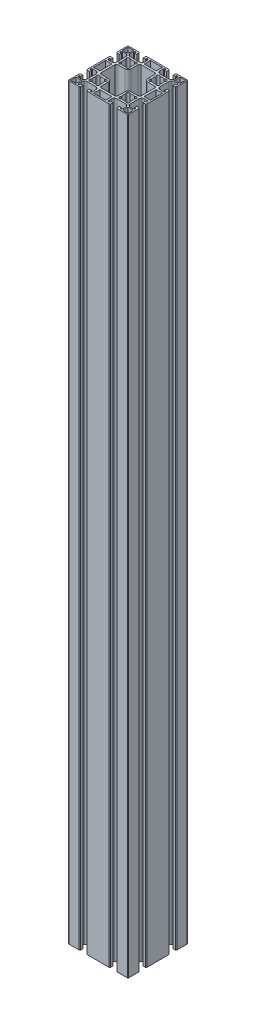
SolidWorks part; units mm, degrees
ref_plane "Front Plane" through (0, 0, 0) normal (0, 0, 1) x (1, 0, 0)
ref_plane "Top Plane" through (0, 0, 0) normal (0, 1, 0) x (1, 0, 0)
ref_plane "Right Plane" through (0, 0, 0) normal (1, 0, 0) x (0, 0, -1)
sketch "Sketch1" plane through (0, 0, 0) normal (0, 1, 0) x (1, 0, 0)
  line L0 (16.5224, 10.1082) -> (17.1083, 10.6941)
  line L2 (14.2799, 13.5226) -> (13.694, 12.9366)
  line L7 (13.694, 19.6541) -> (14.2799, 19.0682)
  line L8 (17.1083, 21.8966) -> (16.5224, 22.4826)
  line L9 (23.2399, 22.4826) -> (22.654, 21.8966)
  line L10 (25.4824, 19.0682) -> (26.0683, 19.6541)
  line L11 (26.0683, 12.9366) -> (25.4824, 13.5226)
  line L12 (22.654, 10.6941) -> (23.2399, 10.1082)
  line L13 (-29.7188, -11.8046) -> (-29.7188, 4.3954)
  line L14 (-38.1188, -11.8046) -> (-29.7188, -11.8046)
  line L15 (-38.1188, 4.3954) -> (-38.1188, -11.8046)
  line L16 (-29.7188, 4.3954) -> (-38.1188, 4.3954)
  line L17 (-23.4776, 10.1082) -> (-22.8917, 10.6941)
  line L18 (-25.7201, 13.5226) -> (-26.306, 12.9366)
  line L19 (-26.306, 19.6541) -> (-25.7201, 19.0682)
  line L20 (-22.8917, 21.8966) -> (-23.4776, 22.4826)
  line L21 (-16.7601, 22.4826) -> (-17.346, 21.8966)
  line L22 (-14.5176, 19.0682) -> (-13.9317, 19.6541)
  line L23 (-13.9317, 12.9366) -> (-14.5176, 13.5226)
  line L24 (-17.346, 10.6941) -> (-16.7601, 10.1082)
  line L26 (23.2399, -17.5174) -> (22.654, -18.1034)
  line L27 (25.4824, -20.9318) -> (26.0683, -20.3459)
  line L28 (26.0683, -27.0634) -> (25.4824, -26.4774)
  line L29 (22.654, -29.3059) -> (23.2399, -29.8918)
  line L30 (16.5224, -29.8918) -> (17.1083, -29.3059)
  line L31 (14.2799, -26.4774) -> (13.694, -27.0634)
  line L32 (13.694, -20.3459) -> (14.2799, -20.9318)
  line L33 (17.1083, -18.1034) -> (16.5224, -17.5174)
  line L41 (-31.3188, -34.9046) -> (-38.5188, -34.9046)
  line L42 (-31.3188, -42.1046) -> (-31.3188, -34.9046)
  line L43 (-38.5188, -42.1046) -> (-31.3188, -42.1046)
  line L44 (-38.5188, -34.9046) -> (-38.5188, -42.1046)
  line L45 (-16.7601, -17.5174) -> (-17.346, -18.1034)
  line L46 (-14.5176, -20.9318) -> (-13.9317, -20.3459)
  line L51 (-13.9317, -27.0634) -> (-14.5176, -26.4774)
  line L52 (-17.346, -29.3059) -> (-16.7601, -29.8918)
  line L53 (-23.4776, -29.8918) -> (-22.8917, -29.3059)
  line L54 (-25.7201, -26.4774) -> (-26.306, -27.0634)
  line L55 (-26.306, -20.3459) -> (-25.7201, -20.9318)
  line L56 (-22.8917, -18.1034) -> (-23.4776, -17.5174)
  line L57 (-38.5188, 27.4954) -> (-31.3188, 27.4954)
  line L58 (-38.5188, 34.6954) -> (-38.5188, 27.4954)
  line L59 (-31.3188, 34.6954) -> (-38.5188, 34.6954)
  line L60 (-31.3188, 27.4954) -> (-31.3188, 34.6954)
  line L61 (38.2812, -34.9046) -> (31.0812, -34.9046)
  line L62 (38.2812, -42.1046) -> (38.2812, -34.9046)
  line L63 (31.0812, -42.1046) -> (38.2812, -42.1046)
  line L64 (31.0812, -34.9046) -> (31.0812, -42.1046)
  line L65 (31.0812, 27.4954) -> (38.2812, 27.4954)
  line L66 (31.0812, 34.6954) -> (31.0812, 27.4954)
  line L67 (38.2812, 34.6954) -> (31.0812, 34.6954)
  line L68 (38.2812, 27.4954) -> (38.2812, 34.6954)
  line L69 (-8.2188, 34.2954) -> (-8.2188, 25.8954)
  line L70 (7.9812, 34.2954) -> (-8.2188, 34.2954)
  line L71 (7.9812, 25.8954) -> (7.9812, 34.2954)
  line L72 (-8.2188, 25.8954) -> (7.9812, 25.8954)
  line L79 (11.0812, -28.5046) -> (11.0812, -18.9046)
  line L80 (-9.3188, -30.5046) -> (9.0812, -30.5046)
  line L81 (-11.3188, -18.9046) -> (-11.3188, -28.5046)
  line L82 (-24.9188, -14.9046) -> (-15.3188, -14.9046)
  line L83 (-26.9188, 5.4954) -> (-26.9188, -12.9046)
  line L84 (-15.3188, 7.4954) -> (-24.9188, 7.4954)
  line L89 (-11.3188, 21.0954) -> (-11.3188, 11.4954)
  line L90 (9.0812, 23.0954) -> (-9.3188, 23.0954)
  line L91 (11.0812, 11.4954) -> (11.0812, 21.0954)
  line L92 (24.6812, 7.4954) -> (15.0812, 7.4954)
  line L93 (26.6812, -12.9046) -> (26.6812, 5.4954)
  line L94 (15.0812, -14.9046) -> (24.6812, -14.9046)
  line L95 (7.9812, -33.3046) -> (-8.2188, -33.3046)
  line L96 (7.9812, -41.7046) -> (7.9812, -33.3046)
  line L97 (-8.2188, -41.7046) -> (7.9812, -41.7046)
  line L98 (-8.2188, -33.3046) -> (-8.2188, -41.7046)
  line L99 (29.4812, 4.3954) -> (29.4812, -11.8046)
  line L100 (37.8812, 4.3954) -> (29.4812, 4.3954)
  line L101 (37.8812, -11.8046) -> (37.8812, 4.3954)
  line L102 (29.4812, -11.8046) -> (37.8812, -11.8046)
  line L103 (39.8812, -42.7046) -> (39.8812, -28.9546)
  line L104 (39.8812, -28.9546) -> (38.8812, -27.9546)
  line L105 (38.8812, -27.9546) -> (35.8812, -27.9546)
  line L106 (35.8812, -27.9546) -> (35.8812, -30.9546)
  line L107 (35.8812, -30.9546) -> (37.4853, -30.9546)
  line L108 (37.9777, -31.5414) -> (37.7979, -32.5609)
  line L109 (36.9116, -33.3046) -> (32.215, -33.3046)
  line L110 (30.0937, -32.4259) -> (29.5598, -31.8921)
  line L111 (28.6812, -29.7708) -> (28.6812, -17.6385)
  line L118 (29.5598, -15.5172) -> (30.0937, -14.9833)
  line L119 (32.215, -14.1046) -> (36.9116, -14.1046)
  line L120 (37.7979, -14.8483) -> (37.9777, -15.8678)
  line L121 (37.4853, -16.4546) -> (35.8812, -16.4546)
  line L122 (35.8812, -16.4546) -> (35.8812, -19.4546)
  line L123 (35.8812, -19.4546) -> (38.8812, -19.4546)
  line L128 (38.8812, -19.4546) -> (39.8812, -18.4546)
  line L129 (39.8812, -18.4546) -> (39.8812, 11.0454)
  line L130 (39.8812, 11.0454) -> (38.8812, 12.0454)
  line L131 (38.8812, 12.0454) -> (35.8812, 12.0454)
  line L132 (35.8812, 12.0454) -> (35.8812, 9.0454)
  line L133 (35.8812, 9.0454) -> (37.4853, 9.0454)
  line L134 (37.9777, 8.4586) -> (37.7979, 7.4391)
  line L135 (36.9116, 6.6954) -> (32.215, 6.6954)
  line L136 (30.0937, 7.5741) -> (29.5598, 8.1079)
  line L137 (28.6812, 10.2292) -> (28.6812, 22.3615)
  line L138 (29.5598, 24.4828) -> (30.0937, 25.0167)
  line L139 (32.215, 25.8954) -> (36.9116, 25.8954)
  line L140 (37.7979, 25.1517) -> (37.9777, 24.1322)
  line L141 (37.4853, 23.5454) -> (35.8812, 23.5454)
  line L142 (35.8812, 23.5454) -> (35.8812, 20.5454)
  line L143 (35.8812, 20.5454) -> (38.8812, 20.5454)
  line L144 (38.8812, 20.5454) -> (39.8812, 21.5454)
  line L145 (39.8812, 21.5454) -> (39.8812, 35.2954)
  line L146 (38.8812, 36.2954) -> (25.1312, 36.2954)
  line L147 (25.1312, 36.2954) -> (24.1312, 35.2954)
  line L148 (24.1312, 35.2954) -> (24.1312, 32.2954)
  line L149 (24.1312, 32.2954) -> (27.1312, 32.2954)
  line L150 (27.1312, 32.2954) -> (27.1312, 33.8995)
  line L157 (27.718, 34.3919) -> (28.7374, 34.2122)
  line L158 (29.4812, 33.3258) -> (29.4812, 28.6292)
  line L159 (28.6025, 26.5079) -> (28.0686, 25.9741)
  line L160 (25.9473, 25.0954) -> (13.815, 25.0954)
  line L161 (11.6937, 25.9741) -> (11.1598, 26.5079)
  line L162 (10.2812, 28.6292) -> (10.2812, 33.3258)
  line L167 (11.0249, 34.2122) -> (12.0443, 34.3919)
  line L172 (12.6312, 33.8995) -> (12.6312, 32.2954)
  line L173 (12.6312, 32.2954) -> (15.6312, 32.2954)
  line L178 (15.6312, 32.2954) -> (15.6312, 35.2954)
  line L179 (15.6312, 35.2954) -> (14.6312, 36.2954)
  line L183 (14.6312, 36.2954) -> (-14.8688, 36.2954)
  line L184 (-14.8688, 36.2954) -> (-15.8688, 35.2954)
  line L189 (-15.8688, 35.2954) -> (-15.8688, 32.2954)
  line L190 (-15.8688, 32.2954) -> (-12.8688, 32.2954)
  line L195 (-12.8688, 32.2954) -> (-12.8688, 33.8995)
  line L196 (-12.282, 34.3919) -> (-11.2626, 34.2122)
  line L198 (-10.5188, 33.3258) -> (-10.5188, 28.6292)
  line L199 (-11.3975, 26.5079) -> (-11.9314, 25.9741)
  line L200 (-14.0527, 25.0954) -> (-26.185, 25.0954)
  line L201 (-28.3063, 25.9741) -> (-28.8402, 26.5079)
  line L202 (-29.7188, 28.6292) -> (-29.7188, 33.3258)
  line L203 (-28.9751, 34.2122) -> (-27.9557, 34.3919)
  line L204 (-27.3688, 33.8995) -> (-27.3688, 32.2954)
  line L205 (-27.3688, 32.2954) -> (-24.3688, 32.2954)
  line L206 (-24.3688, 32.2954) -> (-24.3688, 35.2954)
  line L207 (-24.3688, 35.2954) -> (-25.3688, 36.2954)
  line L208 (-25.3688, 36.2954) -> (-39.1188, 36.2954)
  line L209 (-40.1188, 35.2954) -> (-40.1188, 21.5454)
  line L210 (-40.1188, 21.5454) -> (-39.1188, 20.5454)
  line L211 (-39.1188, 20.5454) -> (-36.1188, 20.5454)
  line L212 (-36.1188, 20.5454) -> (-36.1188, 23.5454)
  line L213 (-36.1188, 23.5454) -> (-37.723, 23.5454)
  line L214 (-38.2154, 24.1322) -> (-38.0356, 25.1517)
  line L215 (-37.1493, 25.8954) -> (-32.4527, 25.8954)
  line L216 (-30.3314, 25.0167) -> (-29.7975, 24.4828)
  line L217 (-28.9188, 22.3615) -> (-28.9188, 10.2292)
  line L218 (-29.7975, 8.1079) -> (-30.3314, 7.5741)
  line L219 (-32.4527, 6.6954) -> (-37.1493, 6.6954)
  line L220 (-38.0356, 7.4391) -> (-38.2154, 8.4586)
  line L221 (-37.723, 9.0454) -> (-36.1188, 9.0454)
  line L222 (-36.1188, 9.0454) -> (-36.1188, 12.0454)
  line L223 (-36.1188, 12.0454) -> (-39.1188, 12.0454)
  line L224 (-39.1188, 12.0454) -> (-40.1188, 11.0454)
  line L225 (-40.1188, 11.0454) -> (-40.1188, -18.4546)
  line L226 (-40.1188, -18.4546) -> (-39.1188, -19.4546)
  line L227 (-39.1188, -19.4546) -> (-36.1188, -19.4546)
  line L228 (-36.1188, -19.4546) -> (-36.1188, -16.4546)
  line L229 (-36.1188, -16.4546) -> (-37.723, -16.4546)
  line L230 (-38.2154, -15.8678) -> (-38.0356, -14.8483)
  line L231 (-37.1493, -14.1046) -> (-32.4527, -14.1046)
  line L232 (-30.3314, -14.9833) -> (-29.7975, -15.5172)
  line L233 (-28.9188, -17.6385) -> (-28.9188, -29.7708)
  line L234 (-29.7975, -31.8921) -> (-30.3314, -32.4259)
  line L235 (-32.4527, -33.3046) -> (-37.1493, -33.3046)
  line L236 (-38.0356, -32.5609) -> (-38.2154, -31.5414)
  line L237 (-37.723, -30.9546) -> (-36.1188, -30.9546)
  line L238 (-36.1188, -30.9546) -> (-36.1188, -27.9546)
  line L239 (-36.1188, -27.9546) -> (-39.1188, -27.9546)
  line L240 (-39.1188, -27.9546) -> (-40.1188, -28.9546)
  line L241 (-40.1188, -28.9546) -> (-40.1188, -42.7046)
  line L242 (-39.1188, -43.7046) -> (-25.3688, -43.7046)
  line L243 (-25.3688, -43.7046) -> (-24.3688, -42.7046)
  line L244 (-24.3688, -42.7046) -> (-24.3688, -39.7046)
  line L245 (-24.3688, -39.7046) -> (-27.3688, -39.7046)
  line L246 (-27.3688, -39.7046) -> (-27.3688, -41.3087)
  line L247 (-27.9557, -41.8011) -> (-28.9751, -41.6214)
  line L248 (-29.7188, -40.7351) -> (-29.7188, -36.0385)
  line L249 (-28.8402, -33.9172) -> (-28.3063, -33.3833)
  line L250 (-26.185, -32.5046) -> (-14.0527, -32.5046)
  line L251 (-11.9314, -33.3833) -> (-11.3975, -33.9172)
  line L252 (-10.5188, -36.0385) -> (-10.5188, -40.7351)
  line L253 (-11.2626, -41.6214) -> (-12.282, -41.8011)
  line L254 (-12.8688, -41.3087) -> (-12.8688, -39.7046)
  line L255 (-12.8688, -39.7046) -> (-15.8688, -39.7046)
  line L256 (-15.8688, -39.7046) -> (-15.8688, -42.7046)
  line L257 (-15.8688, -42.7046) -> (-14.8688, -43.7046)
  line L258 (-14.8688, -43.7046) -> (14.6312, -43.7046)
  line L259 (14.6312, -43.7046) -> (15.6312, -42.7046)
  line L260 (15.6312, -42.7046) -> (15.6312, -39.7046)
  line L261 (15.6312, -39.7046) -> (12.6312, -39.7046)
  line L262 (12.6312, -39.7046) -> (12.6312, -41.3087)
  line L263 (12.0443, -41.8011) -> (11.0249, -41.6214)
  line L264 (10.2812, -40.7351) -> (10.2812, -36.0385)
  line L265 (11.1598, -33.9172) -> (11.6937, -33.3833)
  line L266 (13.815, -32.5046) -> (25.9473, -32.5046)
  line L267 (28.0686, -33.3833) -> (28.6025, -33.9172)
  line L268 (29.4812, -36.0385) -> (29.4812, -40.7351)
  line L269 (28.7374, -41.6214) -> (27.718, -41.8011)
  line L270 (27.1312, -41.3087) -> (27.1312, -39.7046)
  line L271 (27.1312, -39.7046) -> (24.1312, -39.7046)
  line L272 (24.1312, -39.7046) -> (24.1312, -42.7046)
  line L273 (24.1312, -42.7046) -> (25.1312, -43.7046)
  line L274 (25.1312, -43.7046) -> (38.8812, -43.7046)
  arc A0 (17.1083, 10.6941) -> (22.654, 10.6941) centre (19.8812, 16.2954) ccw
  arc A1 (13.694, 12.9366) -> (16.5224, 10.1082) centre (15.1082, 11.5224) ccw
  arc A2 (14.2799, 19.0682) -> (14.2799, 13.5226) centre (19.8812, 16.2954) ccw
  arc A3 (16.5224, 22.4826) -> (13.694, 19.6541) centre (15.1082, 21.0684) ccw
  arc A4 (22.654, 21.8966) -> (17.1083, 21.8966) centre (19.8812, 16.2954) ccw
  arc A5 (26.0683, 19.6541) -> (23.2399, 22.4826) centre (24.6541, 21.0684) ccw
  arc A6 (25.4824, 13.5226) -> (25.4824, 19.0682) centre (19.8812, 16.2954) ccw
  arc A7 (23.2399, 10.1082) -> (26.0683, 12.9366) centre (24.6541, 11.5224) ccw
  arc A8 (-22.8917, 10.6941) -> (-17.346, 10.6941) centre (-20.1188, 16.2954) ccw
  arc A9 (-26.306, 12.9366) -> (-23.4776, 10.1082) centre (-24.8918, 11.5224) ccw
  arc A10 (-25.7201, 19.0682) -> (-25.7201, 13.5226) centre (-20.1188, 16.2954) ccw
  arc A11 (-23.4776, 22.4826) -> (-26.306, 19.6541) centre (-24.8918, 21.0684) ccw
  arc A12 (-17.346, 21.8966) -> (-22.8917, 21.8966) centre (-20.1188, 16.2954) ccw
  arc A13 (-13.9317, 19.6541) -> (-16.7601, 22.4826) centre (-15.3459, 21.0684) ccw
  arc A14 (-14.5176, 13.5226) -> (-14.5176, 19.0682) centre (-20.1188, 16.2954) ccw
  arc A15 (-16.7601, 10.1082) -> (-13.9317, 12.9366) centre (-15.3459, 11.5224) ccw
  arc A50 (22.654, -18.1034) -> (17.1083, -18.1034) centre (19.8812, -23.7046) ccw
  arc A51 (26.0683, -20.3459) -> (23.2399, -17.5174) centre (24.6541, -18.9316) ccw
  arc A52 (25.4824, -26.4774) -> (25.4824, -20.9318) centre (19.8812, -23.7046) ccw
  arc A53 (23.2399, -29.8918) -> (26.0683, -27.0634) centre (24.6541, -28.4776) ccw
  arc A54 (17.1083, -29.3059) -> (22.654, -29.3059) centre (19.8812, -23.7046) ccw
  arc A55 (13.694, -27.0634) -> (16.5224, -29.8918) centre (15.1082, -28.4776) ccw
  arc A56 (14.2799, -20.9318) -> (14.2799, -26.4774) centre (19.8812, -23.7046) ccw
  arc A57 (16.5224, -17.5174) -> (13.694, -20.3459) centre (15.1082, -18.9316) ccw
  arc A58 (-17.346, -18.1034) -> (-22.8917, -18.1034) centre (-20.1188, -23.7046) ccw
  arc A59 (-13.9317, -20.3459) -> (-16.7601, -17.5174) centre (-15.3459, -18.9316) ccw
  arc A60 (-14.5176, -26.4774) -> (-14.5176, -20.9318) centre (-20.1188, -23.7046) ccw
  arc A61 (-16.7601, -29.8918) -> (-13.9317, -27.0634) centre (-15.3459, -28.4776) ccw
  arc A62 (-22.8917, -29.3059) -> (-17.346, -29.3059) centre (-20.1188, -23.7046) ccw
  arc A63 (-26.306, -27.0634) -> (-23.4776, -29.8918) centre (-24.8918, -28.4776) ccw
  arc A64 (-25.7201, -20.9318) -> (-25.7201, -26.4774) centre (-20.1188, -23.7046) ccw
  arc A65 (-23.4776, -17.5174) -> (-26.306, -20.3459) centre (-24.8918, -18.9316) ccw
  arc A66 (15.0812, -14.9046) -> (11.0812, -18.9046) centre (15.0812, -18.9046) ccw
  arc A67 (9.0812, -30.5046) -> (11.0812, -28.5046) centre (9.0812, -28.5046) ccw
  arc A68 (-11.3188, -28.5046) -> (-9.3188, -30.5046) centre (-9.3188, -28.5046) ccw
  arc A69 (-11.3188, -18.9046) -> (-15.3188, -14.9046) centre (-15.3188, -18.9046) ccw
  arc A70 (-26.9188, -12.9046) -> (-24.9188, -14.9046) centre (-24.9188, -12.9046) ccw
  arc A71 (-24.9188, 7.4954) -> (-26.9188, 5.4954) centre (-24.9188, 5.4954) ccw
  arc A72 (-15.3188, 7.4954) -> (-11.3188, 11.4954) centre (-15.3188, 11.4954) ccw
  arc A73 (-9.3188, 23.0954) -> (-11.3188, 21.0954) centre (-9.3188, 21.0954) ccw
  arc A74 (11.0812, 21.0954) -> (9.0812, 23.0954) centre (9.0812, 21.0954) ccw
  arc A75 (11.0812, 11.4954) -> (15.0812, 7.4954) centre (15.0812, 11.4954) ccw
  arc A76 (26.6812, 5.4954) -> (24.6812, 7.4954) centre (24.6812, 5.4954) ccw
  arc A77 (24.6812, -14.9046) -> (26.6812, -12.9046) centre (24.6812, -12.9046) ccw
  arc A78 (38.8812, -43.7046) -> (39.8812, -42.7046) centre (38.8812, -42.7046) ccw
  arc A79 (37.9777, -31.5414) -> (37.4853, -30.9546) centre (37.4853, -31.4546) ccw
  arc A80 (36.9116, -33.3046) -> (37.7979, -32.5609) centre (36.9116, -32.4046) ccw
  arc A81 (30.0937, -32.4259) -> (32.215, -33.3046) centre (32.215, -30.3046) ccw
  arc A82 (28.6812, -29.7708) -> (29.5598, -31.8921) centre (31.6812, -29.7708) ccw
  arc A83 (29.5598, -15.5172) -> (28.6812, -17.6385) centre (31.6812, -17.6385) ccw
  arc A84 (32.215, -14.1046) -> (30.0937, -14.9833) centre (32.215, -17.1046) ccw
  arc A85 (37.7979, -14.8483) -> (36.9116, -14.1046) centre (36.9116, -15.0046) ccw
  arc A86 (37.4853, -16.4546) -> (37.9777, -15.8678) centre (37.4853, -15.9546) ccw
  arc A87 (37.9777, 8.4586) -> (37.4853, 9.0454) centre (37.4853, 8.5454) ccw
  arc A88 (36.9116, 6.6954) -> (37.7979, 7.4391) centre (36.9116, 7.5954) ccw
  arc A89 (30.0937, 7.5741) -> (32.215, 6.6954) centre (32.215, 9.6954) ccw
  arc A90 (28.6812, 10.2292) -> (29.5598, 8.1079) centre (31.6812, 10.2292) ccw
  arc A91 (29.5598, 24.4828) -> (28.6812, 22.3615) centre (31.6812, 22.3615) ccw
  arc A92 (32.215, 25.8954) -> (30.0937, 25.0167) centre (32.215, 22.8954) ccw
  arc A93 (37.7979, 25.1517) -> (36.9116, 25.8954) centre (36.9116, 24.9954) ccw
  arc A94 (37.4853, 23.5454) -> (37.9777, 24.1322) centre (37.4853, 24.0454) ccw
  arc A95 (39.8812, 35.2954) -> (38.8812, 36.2954) centre (38.8812, 35.2954) ccw
  arc A96 (27.718, 34.3919) -> (27.1312, 33.8995) centre (27.6312, 33.8995) ccw
  arc A97 (29.4812, 33.3258) -> (28.7374, 34.2122) centre (28.5812, 33.3258) ccw
  arc A98 (28.6025, 26.5079) -> (29.4812, 28.6292) centre (26.4812, 28.6292) ccw
  arc A99 (25.9473, 25.0954) -> (28.0686, 25.9741) centre (25.9473, 28.0954) ccw
  arc A100 (11.6937, 25.9741) -> (13.815, 25.0954) centre (13.815, 28.0954) ccw
  arc A101 (10.2812, 28.6292) -> (11.1598, 26.5079) centre (13.2812, 28.6292) ccw
  arc A102 (11.0249, 34.2122) -> (10.2812, 33.3258) centre (11.1812, 33.3258) ccw
  arc A103 (12.6312, 33.8995) -> (12.0443, 34.3919) centre (12.1312, 33.8995) ccw
  arc A104 (-12.282, 34.3919) -> (-12.8688, 33.8995) centre (-12.3688, 33.8995) ccw
  arc A105 (-10.5188, 33.3258) -> (-11.2626, 34.2122) centre (-11.4188, 33.3258) ccw
  arc A106 (-11.3975, 26.5079) -> (-10.5188, 28.6292) centre (-13.5188, 28.6292) ccw
  arc A107 (-14.0527, 25.0954) -> (-11.9314, 25.9741) centre (-14.0527, 28.0954) ccw
  arc A108 (-28.3063, 25.9741) -> (-26.185, 25.0954) centre (-26.185, 28.0954) ccw
  arc A109 (-29.7188, 28.6292) -> (-28.8402, 26.5079) centre (-26.7188, 28.6292) ccw
  arc A110 (-28.9751, 34.2122) -> (-29.7188, 33.3258) centre (-28.8188, 33.3258) ccw
  arc A111 (-27.3688, 33.8995) -> (-27.9557, 34.3919) centre (-27.8688, 33.8995) ccw
  arc A112 (-39.1188, 36.2954) -> (-40.1188, 35.2954) centre (-39.1188, 35.2954) ccw
  arc A113 (-38.2154, 24.1322) -> (-37.723, 23.5454) centre (-37.723, 24.0454) ccw
  arc A114 (-37.1493, 25.8954) -> (-38.0356, 25.1517) centre (-37.1493, 24.9954) ccw
  arc A115 (-30.3314, 25.0167) -> (-32.4527, 25.8954) centre (-32.4527, 22.8954) ccw
  arc A116 (-28.9188, 22.3615) -> (-29.7975, 24.4828) centre (-31.9188, 22.3615) ccw
  arc A117 (-29.7975, 8.1079) -> (-28.9188, 10.2292) centre (-31.9188, 10.2292) ccw
  arc A118 (-32.4527, 6.6954) -> (-30.3314, 7.5741) centre (-32.4527, 9.6954) ccw
  arc A119 (-38.0356, 7.4391) -> (-37.1493, 6.6954) centre (-37.1493, 7.5954) ccw
  arc A120 (-37.723, 9.0454) -> (-38.2154, 8.4586) centre (-37.723, 8.5454) ccw
  arc A121 (-38.2154, -15.8678) -> (-37.723, -16.4546) centre (-37.723, -15.9546) ccw
  arc A122 (-37.1493, -14.1046) -> (-38.0356, -14.8483) centre (-37.1493, -15.0046) ccw
  arc A123 (-30.3314, -14.9833) -> (-32.4527, -14.1046) centre (-32.4527, -17.1046) ccw
  arc A124 (-28.9188, -17.6385) -> (-29.7975, -15.5172) centre (-31.9188, -17.6385) ccw
  arc A125 (-29.7975, -31.8921) -> (-28.9188, -29.7708) centre (-31.9188, -29.7708) ccw
  arc A126 (-32.4527, -33.3046) -> (-30.3314, -32.4259) centre (-32.4527, -30.3046) ccw
  arc A127 (-38.0356, -32.5609) -> (-37.1493, -33.3046) centre (-37.1493, -32.4046) ccw
  arc A128 (-37.723, -30.9546) -> (-38.2154, -31.5414) centre (-37.723, -31.4546) ccw
  arc A129 (-40.1188, -42.7046) -> (-39.1188, -43.7046) centre (-39.1188, -42.7046) ccw
  arc A130 (-27.9557, -41.8011) -> (-27.3688, -41.3087) centre (-27.8688, -41.3087) ccw
  arc A131 (-29.7188, -40.7351) -> (-28.9751, -41.6214) centre (-28.8188, -40.7351) ccw
  arc A132 (-28.8402, -33.9172) -> (-29.7188, -36.0385) centre (-26.7188, -36.0385) ccw
  arc A133 (-26.185, -32.5046) -> (-28.3063, -33.3833) centre (-26.185, -35.5046) ccw
  arc A134 (-11.9314, -33.3833) -> (-14.0527, -32.5046) centre (-14.0527, -35.5046) ccw
  arc A135 (-10.5188, -36.0385) -> (-11.3975, -33.9172) centre (-13.5188, -36.0385) ccw
  arc A136 (-11.2626, -41.6214) -> (-10.5188, -40.7351) centre (-11.4188, -40.7351) ccw
  arc A137 (-12.8688, -41.3087) -> (-12.282, -41.8011) centre (-12.3688, -41.3087) ccw
  arc A138 (12.0443, -41.8011) -> (12.6312, -41.3087) centre (12.1312, -41.3087) ccw
  arc A139 (10.2812, -40.7351) -> (11.0249, -41.6214) centre (11.1812, -40.7351) ccw
  arc A140 (11.1598, -33.9172) -> (10.2812, -36.0385) centre (13.2812, -36.0385) ccw
  arc A141 (13.815, -32.5046) -> (11.6937, -33.3833) centre (13.815, -35.5046) ccw
  arc A142 (28.0686, -33.3833) -> (25.9473, -32.5046) centre (25.9473, -35.5046) ccw
  arc A143 (29.4812, -36.0385) -> (28.6025, -33.9172) centre (26.4812, -36.0385) ccw
  arc A144 (28.7374, -41.6214) -> (29.4812, -40.7351) centre (28.5812, -40.7351) ccw
  arc A145 (27.1312, -41.3087) -> (27.718, -41.8011) centre (27.6312, -41.3087) ccw
extrude "Boss-Extrude1" add sketch "Sketch1" along normal blind 1000
